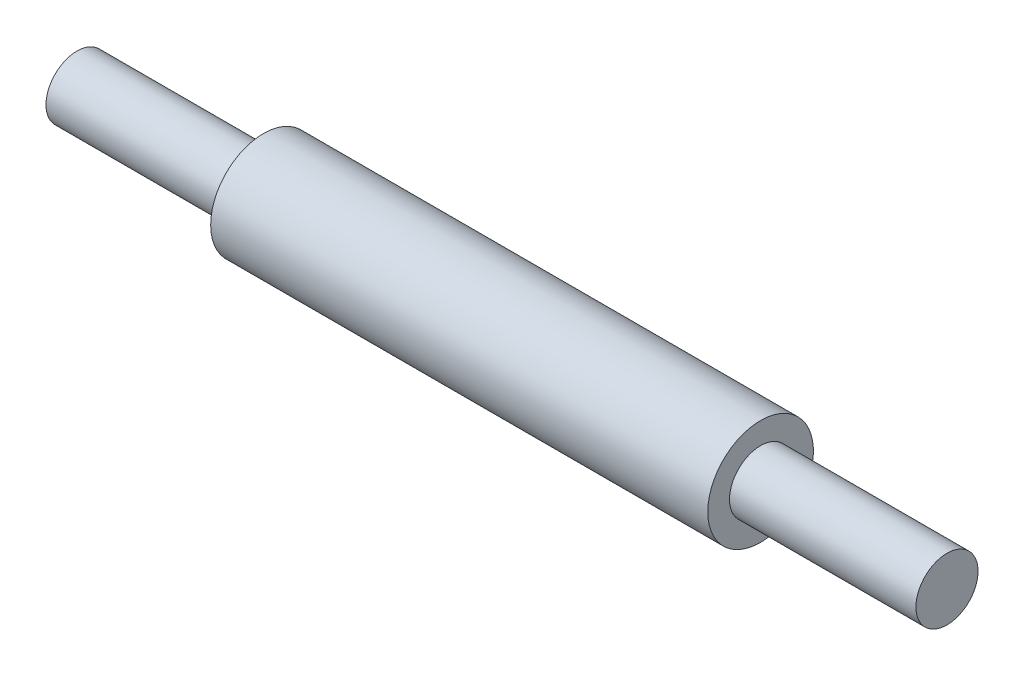
SolidWorks part; units mm, degrees
ref_plane "Front Plane" through (0, 0, 0) normal (0, 0, 1) x (1, 0, 0)
ref_plane "Top Plane" through (0, 0, 0) normal (0, 1, 0) x (1, 0, 0)
ref_plane "Right Plane" through (0, 0, 0) normal (1, 0, 0) x (0, 0, -1)
sketch "Sketch1" plane through (0, 0, 0) normal (0, 1, 0) x (1, 0, 0)
  line L0 (-70, 0) -> (70, 0) construction
  line L1 (0, 43.7451) -> (0, -43.7451) construction
  line L2 (0, 0) -> (0, 8.5) construction
  line L3 (40, 8.5) -> (-40, 8.5)
  line L4 (-40, 8.5) -> (-40, 5)
  line L5 (-40, 5) -> (-70, 5)
  line L6 (-70, 5) -> (-70, 0)
  line L7 (-70, 0) -> (70, 0)
  line L8 (70, 5) -> (70, 0)
  line L9 (40, 5) -> (70, 5)
  line L10 (40, 8.5) -> (40, 5)
  point P11 (0, 0)
  dimension "D1" = 140
  dimension "D2" = 8.5
  dimension "D3" = 5
  dimension "D4" = 40
revolve "Revolve1" add sketch "Sketch1" angle 360 about L7
